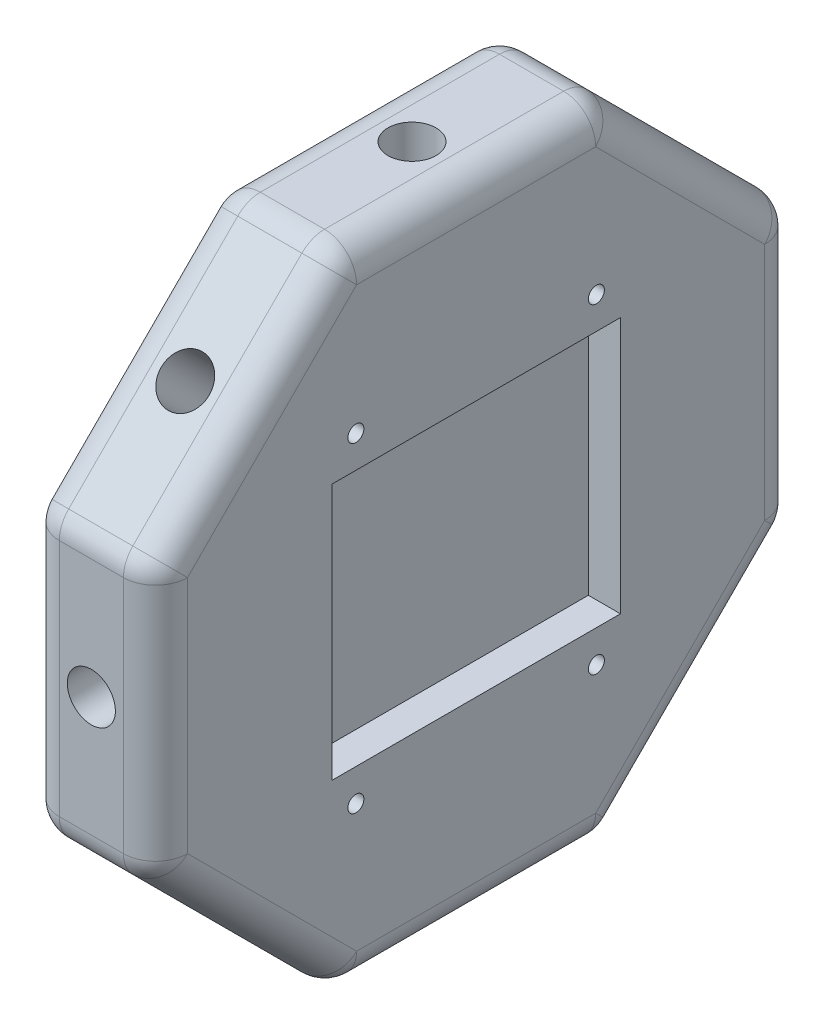
SolidWorks part; units mm, degrees
material "Hexcel AS4C (3000 Filaments)"
ref_plane "Front Plane" through (0, 0, 0) normal (0, 0, 1) x (1, 0, 0)
ref_plane "Top Plane" through (0, 0, 0) normal (0, 1, 0) x (1, 0, 0)
ref_plane "Right Plane" through (0, 0, 0) normal (1, 0, 0) x (0, 0, -1)
sketch "Sketch4" plane through (0, 0, 0) normal (1, 0, 0) x (0, 0, -1)
  line L1 (82.8427, 200) -> (-82.8427, 200)
  line L2 (-82.8427, 200) -> (-200, 82.8427)
  line L3 (-200, 82.8427) -> (-200, -82.8427)
  line L4 (-200, -82.8427) -> (-82.8427, -200)
  line L5 (-82.8427, -200) -> (82.8427, -200)
  line L6 (82.8427, -200) -> (200, -82.8427)
  line L7 (200, -82.8427) -> (200, 82.8427)
  line L8 (200, 82.8427) -> (82.8427, 200)
  circle A0 centre (0, 0) radius 200 construction
  dimension "D1" = 400
extrude "Boss-Extrude2" add sketch "Sketch4" along normal blind 80
fillet "Fillet2" radius 20 24 edges at (40, 82.8427, -200) (40, 200, -82.8427) (40, 200, 82.8427) (40, 82.8427, 200) (40, -82.8427, 200) (40, -200, 82.8427) (40, -200, -82.8427) (40, -82.8427, -200) (0, 200, 0) (0, 141.4214, 141.4214) (0, 0, 200) (0, -141.4214, 141.4214) (0, -200, 0) (0, -141.4214, -141.4214) (0, 0, -200) (0, 141.4214, -141.4214) (80, 0, -200) (80, -141.4214, -141.4214) (80, -200, 0) (80, -141.4214, 141.4214) (80, 0, 200) (80, 141.4214, 141.4214) (80, 200, 0) (80, 141.4214, -141.4214)
sketch "Sketch5" plane through (0, -141.4214, -141.4214) normal (0, -0.7071, -0.7071) x (1, 0, 0)
  circle A0 centre (40, 0) radius 15
  dimension "D1" = 30
extrude "Cut-Extrude2" cut sketch "Sketch5" against normal blind 50 contours A0
pattern_circular "CirPattern3" count 8 over 360 about axis through (0, 0, 0) along (1, 0, 0) of "Cut-Extrude2"
sketch "Sketch6" plane through (0, 0, 0) normal (-1, 0, 0) x (0, 0, 1)
  line L0 (181.6629, 0) -> (-175.3882, 0) construction
  line L2 (0, 181.4962) -> (0, -178.5626) construction
  circle A5 centre (75, 100) radius 5
  circle A6 centre (-75, 100) radius 5
  circle A7 centre (-75, -100) radius 5
  circle A8 centre (75, -100) radius 5
  point P0 (0, 0)
  dimension "D1" = 75
  dimension "D2" = 10
  dimension "D3" = 100
extrude "Cut-Extrude3" cut sketch "Sketch6" against normal through all
sketch "Sketch7" plane through (80, 0, 0) normal (1, 0, 0) x (0, 0, -1)
  line L1 (-90, -80) -> (90, -80)
  line L2 (-90, -80) -> (-90, 80)
  line L3 (-90, 80) -> (90, 80)
  line L4 (90, -80) -> (90, 80)
  line L5 (-90, -80) -> (90, 80) construction
  line L6 (-90, 80) -> (90, -80) construction
  point P1 (0, 0)
  dimension "D1" = 160
  dimension "D2" = 180
extrude "Cut-Extrude4" cut sketch "Sketch7" against normal blind 20
chamfer "Chamfer1" distance 10 angle 45 4 edges at (0, 100, 80) (0, 100, -80) (0, -100, -70) (0, -100, 70)
